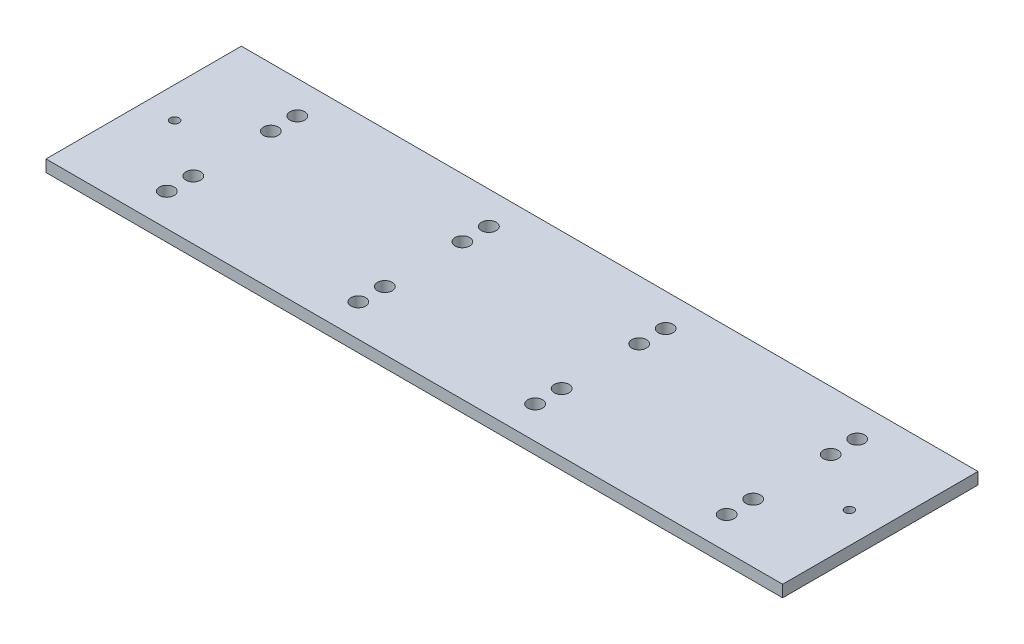
SolidWorks part; units mm, degrees
material "1060 Alloy"
ref_plane "Front Plane" through (0, 0, 0) normal (0, 0, 1) x (1, 0, 0)
ref_plane "Top Plane" through (0, 0, 0) normal (0, 1, 0) x (1, 0, 0)
ref_plane "Right Plane" through (0, 0, 0) normal (1, 0, 0) x (0, 0, -1)
sketch "Sketch1" plane through (0, 0, 0) normal (0, 1, 0) x (1, 0, 0)
  line L0 (0, -44.7868) -> (0, 44.7868) construction
  line L1 (-125, 33.15) -> (125, 33.15)
  line L2 (-125, 33.15) -> (-125, -33.15)
  line L3 (-125, -33.15) -> (125, -33.15)
  line L4 (125, 33.15) -> (125, -33.15)
  line L5 (-44.2539, 0) -> (44.2539, 0) construction
  dimension "D1" = 66.3
  dimension "D2" = 250
  dimension "D3" = 125
  dimension "D4" = 33.15
extrude "Boss-Extrude1" add sketch "Sketch1" along normal blind 4
hole_wizard "Ø5.0mm Dowel Hole1" [suppressed] positions "Sketch2" profile "Sketch3" hole size "Ø5.0" standard "ISO"
sketch "Sketch2" plane through (0, 4, 0) normal (0, 1, 0) x (1, 0, 0)
  line L0 (125, 33.15) -> (-125, 33.15) construction
  line L1 (-125, 33.15) -> (-125, -33.15) construction
  point P0 (-95, 23.15)
  point P2 (-95, 14.15)
  dimension "D1" = 10
  dimension "D2" = 9
  dimension "D3" = 30
sketch "Sketch3" plane through (-95, 4, -23.15) normal (1, 0, 0) x (0, 0, 1)
  line L0 (0, 0) -> (0, 51.5022)
  line L1 (0, 51.5022) -> (2.5, 50)
  line L2 (2.5, 50) -> (2.5, 0)
  line L5 (2.5, 0) -> (0, 0)
  line L10 (0, 51.5022) -> (-2.5, 50) construction
  line L11 (0, -6.35) -> (0, 107.95) construction
  dimension "Hole Dia." = 5
  dimension "Hole Depth" = 50
  dimension "Drill Angle" = 118
hole_wizard "Ø3.0mm Dowel Hole1" positions "Sketch4" profile "Sketch5" hole size "Ø3.0" standard "ISO"
sketch "Sketch4" plane through (0, 4, 0) normal (0, 1, 0) x (1, 0, 0)
  line L0 (-125, 33.15) -> (-125, -33.15) construction
  line L1 (-44.2539, 0) -> (44.2539, 0) construction
  point P0 (-114.5, 0)
  dimension "D1" = 10.5
  dimension "D2" = 0
sketch "Sketch5" plane through (-114.5, 4, 0) normal (1, 0, 0) x (0, 0, 1)
  line L0 (0, 0) -> (0, 100.9013)
  line L1 (0, 100.9013) -> (1.5, 100)
  line L2 (1.5, 100) -> (1.5, 0)
  line L5 (1.5, 0) -> (0, 0)
  line L10 (0, 100.9013) -> (-1.5, 100) construction
  line L11 (0, -6.35) -> (0, 107.95) construction
  dimension "Hole Dia." = 3
  dimension "Hole Depth" = 100
  dimension "Drill Angle" = 118
pattern_linear "LPattern1" [suppressed] count 2 spacing 65
mirror "Mirror1" [suppressed] about plane through (0, 0, 0) normal (1, 0, 0)
mirror "Mirror2" [suppressed] about plane through (0, 0, 0) normal (0, 0, 1)
hole_wizard "Ø5.0mm Dowel Hole2" positions "Sketch6" profile "Sketch7" hole size "Ø5.0" standard "ISO"
sketch "Sketch6" plane through (0, 4, 0) normal (0, 1, 0) x (1, 0, 0)
  line L0 (125, 33.15) -> (-125, 33.15) construction
  line L1 (-125, 33.15) -> (-125, -33.15) construction
  point P0 (-95, 22.15)
  point P2 (-95, 13.15)
  dimension "D1" = 11
  dimension "D2" = 30
  dimension "D3" = 0
  dimension "D4" = 9
sketch "Sketch7" plane through (-95, 4, -22.15) normal (1, 0, 0) x (0, 0, 1)
  line L0 (0, 0) -> (0, 51.5022)
  line L1 (0, 51.5022) -> (2.5, 50)
  line L2 (2.5, 50) -> (2.5, 0)
  line L5 (2.5, 0) -> (0, 0)
  line L10 (0, 51.5022) -> (-2.5, 50) construction
  line L11 (0, -6.35) -> (0, 107.95) construction
  dimension "Hole Dia." = 5
  dimension "Hole Depth" = 50
  dimension "Drill Angle" = 118
pattern_linear "LPattern2" count 2 spacing 65 along (1, 0, 0) of "Ø5.0mm Dowel Hole2"
mirror "Mirror3" about plane through (0, 0, 0) normal (1, 0, 0) of "Ø3.0mm Dowel Hole1", "LPattern2", "Ø5.0mm Dowel Hole2"
mirror "Mirror4" about plane through (0, 0, 0) normal (0, 0, 1) of "Mirror3", "Ø5.0mm Dowel Hole2", "LPattern2"
